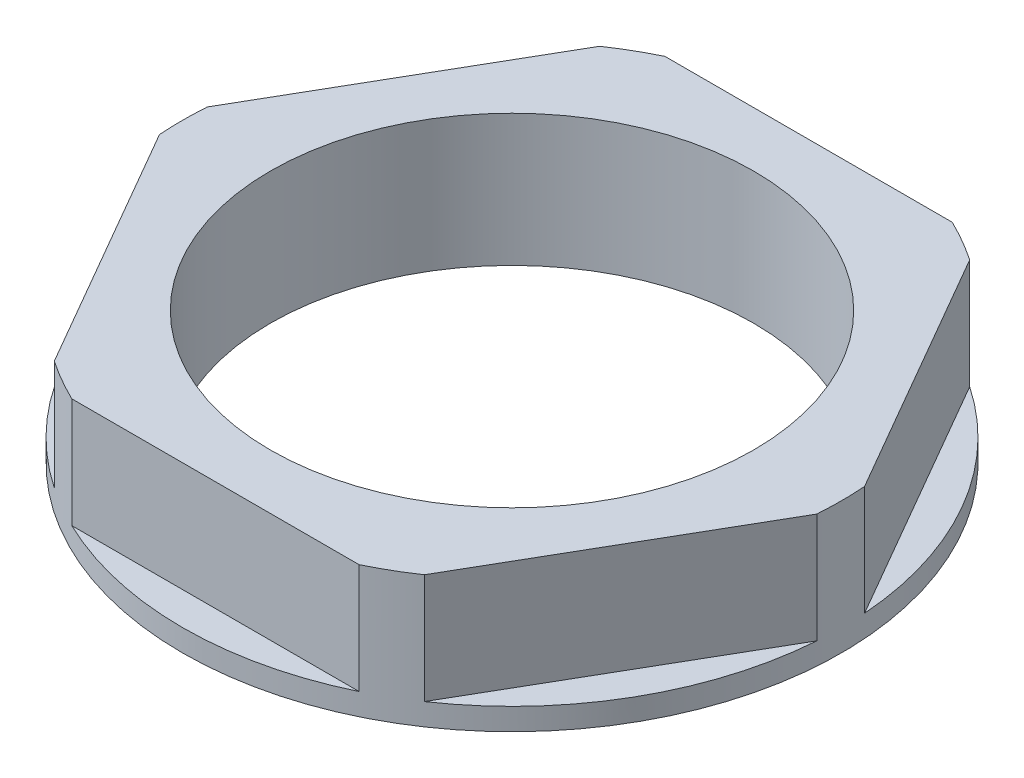
SolidWorks part; units mm, degrees
material "PVC hart"
ref_plane "Ebene vorne" through (0, 0, 0) normal (0, 0, 1) x (1, 0, 0)
ref_plane "Ebene oben" through (0, 0, 0) normal (0, 1, 0) x (1, 0, 0)
ref_plane "Ebene rechts" through (0, 0, 0) normal (1, 0, 0) x (0, 0, -1)
sketch "Skizze1" plane through (0, 0, 0) normal (0, 1, 0) x (1, 0, 0)
  circle A0 centre (0, 0) radius 15
  circle A1 centre (0, 0) radius 11
  dimension "D1" = 30
  dimension "D2" = 22
extrude "Aufsatz-Linear austragen1" add sketch "Skizze1" along normal blind 1
sketch "Skizze2" plane through (0, 1, 0) normal (0, 1, 0) x (1, 0, 0)
  line L1 (15.5885, 0) -> (7.7942, 13.5)
  line L2 (7.7942, 13.5) -> (-7.7942, 13.5)
  line L3 (-7.7942, 13.5) -> (-15.5885, 0)
  line L4 (-15.5885, 0) -> (-7.7942, -13.5)
  line L5 (-7.7942, -13.5) -> (7.7942, -13.5)
  line L6 (7.7942, -13.5) -> (15.5885, 0)
  circle A0 centre (0, 0) radius 11
  circle A1 centre (0, 0) radius 11 construction
  circle A2 centre (0, 0) radius 13.5 construction
  dimension "D1" = 27
extrude "Aufsatz-Linear austragen2" add sketch "Skizze2" along normal blind 5
sketch "Skizze3" plane through (0, 6, 0) normal (0, 1, 0) x (1, 0, 0)
  circle A0 centre (0, 0) radius 15.5885
  circle A1 centre (0, 0) radius 15
  arc A2 (-8.4222, 12.4124) -> (-14.9605, 1.0876) centre (0, 0) ccw construction
  circle A3 centre (0, 0) radius 15 construction
  point P5 (15, 0)
extrude "Schnitt-Linear austragen2" cut sketch "Skizze3" against normal through all
